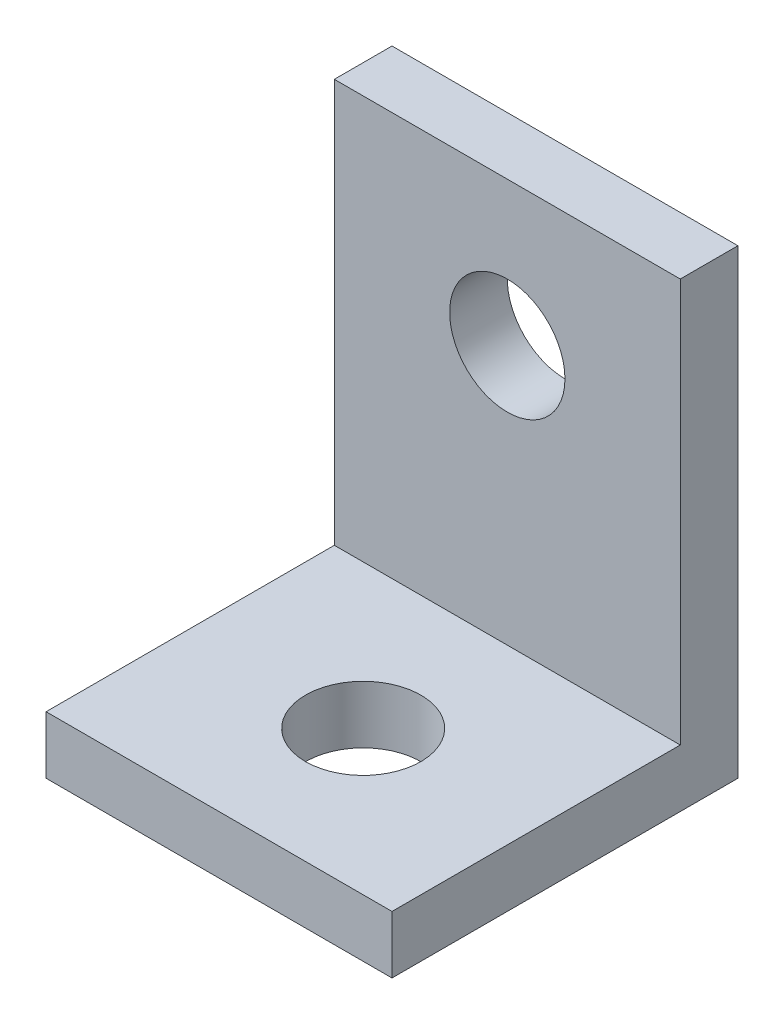
SolidWorks part; units mm, degrees
ref_plane "Front" through (0, 0, 0) normal (0, 0, 1) x (1, 0, 0)
ref_plane "Top" through (0, 0, 0) normal (0, 1, 0) x (1, 0, 0)
ref_plane "Right" through (0, 0, 0) normal (1, 0, 0) x (0, 0, -1)
sketch "Sketch1" plane through (0, 0, 0) normal (0, 1, 0) x (1, 0, 0)
  line L1 (0, 0) -> (19.05, 0)
  line L2 (0, 0) -> (0, -19.05)
  line L3 (0, -19.05) -> (19.05, -19.05)
  line L4 (19.05, 0) -> (19.05, -19.05)
  dimension "D1" = 19.05
  dimension "D2" = 19.05
extrude "Boss-Extrude1" add sketch "Sketch1" along normal blind 3.175
sketch "Sketch2" plane through (0, 3.175, 0) normal (0, 1, 0) x (1, 0, 0)
  line L0 (19.05, -19.05) -> (19.05, 0) construction
  line L1 (0, 0) -> (19.05, 0)
  line L2 (0, 0) -> (0, -3.175)
  line L3 (0, -3.175) -> (19.05, -3.175)
  line L4 (19.05, 0) -> (19.05, -3.175)
  dimension "D1" = 3.175
extrude "Boss-Extrude2" add sketch "Sketch2" along normal blind 22.225
sketch "Sketch3" plane through (0, 3.175, 0) normal (0, 1, 0) x (1, 0, 0)
  line L1 (0, -19.05) -> (19.05, -19.05) construction
  line L2 (0, -3.175) -> (0, -19.05) construction
  circle A0 centre (9.525, -11.1125) radius 3.175
  dimension "D1" = 6.35
  dimension "D2" = 7.9375
  dimension "D3" = 9.525
extrude "Cut-Extrude1" cut sketch "Sketch3" against normal up to next
sketch "Sketch4" plane through (0, 0, 3.175) normal (0, 0, 1) x (1, 0, 0)
  line L0 (0, 25.4) -> (19.05, 25.4) construction
  line L1 (0, 25.4) -> (0, 3.175) construction
  circle A0 centre (9.525, 17.4625) radius 3.175
  dimension "D1" = 6.35
  dimension "D2" = 7.9375
  dimension "D3" = 9.525
extrude "Cut-Extrude2" cut sketch "Sketch4" against normal up to next contours A0
